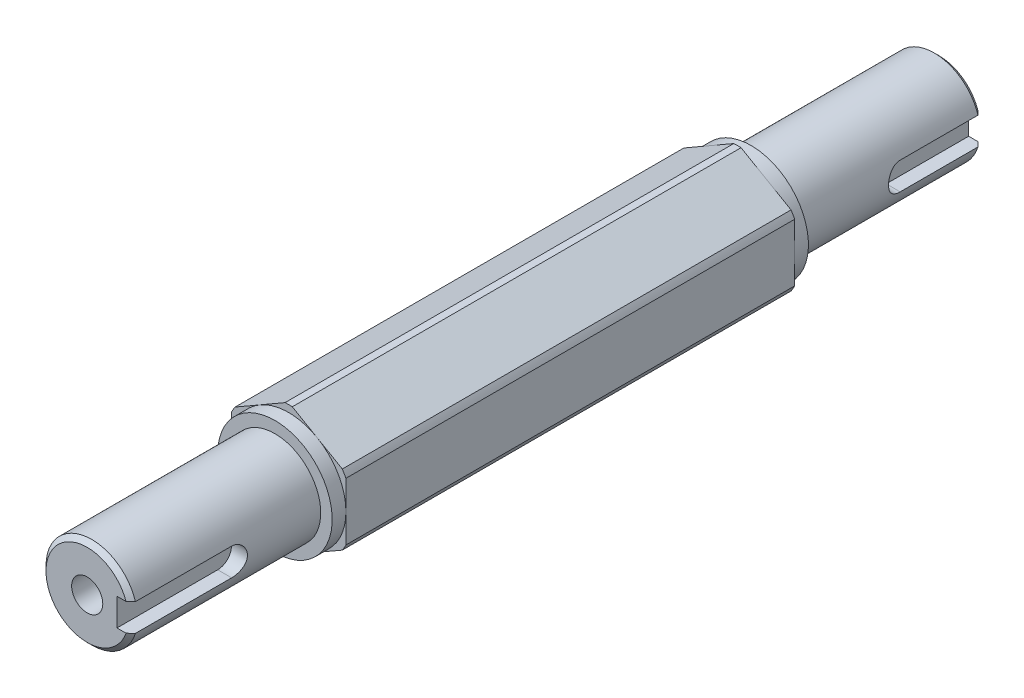
SolidWorks part; units mm, degrees
ref_plane "Front Plane" through (0, 0, 0) normal (0, 0, 1) x (1, 0, 0)
ref_plane "Top Plane" through (0, 0, 0) normal (0, 1, 0) x (1, 0, 0)
ref_plane "Right Plane" through (0, 0, 0) normal (1, 0, 0) x (0, 0, -1)
sketch "Sketch1" plane through (0, 0, 0) normal (0, 0, 1) x (1, 0, 0)
  line L1 (0, 14.4338) -> (-12.5, 7.2169)
  line L2 (-12.5, 7.2169) -> (-12.5, -7.2169)
  line L3 (-12.5, -7.2169) -> (0, -14.4338)
  line L4 (0, -14.4338) -> (12.5, -7.2169)
  line L5 (12.5, -7.2169) -> (12.5, 7.2169)
  line L6 (12.5, 7.2169) -> (0, 14.4338)
  circle A0 centre (0, 0) radius 12.5 construction
  circle A1 centre (0, 0) radius 14
  dimension "D1" = 28
  dimension "D2" = 25
extrude "Boss-Extrude1" add sketch "Sketch1" along normal mid plane 98 contours L5 A1 L6 L1 L2 L3 L4
sketch "Sketch2" plane through (0, 0, 0) normal (1, 0, 0) x (0, 0, -1)
  line L0 (70.7525, 0) -> (-133.0929, 0) construction
  line L1 (-93, 0) -> (-93, 10)
  line L2 (-93, 10) -> (-52, 10)
  line L4 (-49, 12.5) -> (-49, 0)
  line L5 (-49, 0) -> (-93, 0)
  line L6 (52, 10) -> (93, 10)
  line L7 (49, -6.3048) -> (49, 6.3048) construction
  line L8 (93, 10) -> (93, 0)
  line L11 (93, 0) -> (49, 0)
  line L12 (49, 0) -> (49, 12.5)
  line L14 (-52, 10) -> (-52, 12.5)
  line L15 (-52, 12.5) -> (-49, 12.5)
  line L16 (-49, 7.6729) -> (-49, 13.9777) construction
  line L17 (52, 10) -> (52, 12.5)
  line L18 (52, 12.5) -> (49, 12.5)
  dimension "D1" = 20
  dimension "D2" = 25
  dimension "D3" = 104
  dimension "D4" = 41
  dimension "D7" = 41
revolve "Revolve1" add sketch "Sketch2" angle 360 about L0
chamfer "Chamfer1" distance 1 angle 45 2 edges at (-10, 0, 93) (-10, 0, -93)
hole_wizard "M8 Tapped Hole1" positions "3DSketch1" profile "Sketch3" tap size "M8" standard "ISO"
sketch3d "3DSketch1"
  circle A0 centre (0, 0, 93) radius 9 construction
  point P0 (0, 0, 93)
  point P5 (0, 0, 102)
sketch "Sketch3" plane through (0, 0, 93) normal (1, 0, 0) x (0, -1, 0)
  line L0 (0, 0) -> (0, 21.7929)
  line L1 (0, 21.7929) -> (3.4, 19.75)
  line L2 (3.4, 19.75) -> (3.4, 0)
  line L5 (3.4, 0) -> (0, 0)
  line L10 (0, 21.7929) -> (-3.4, 19.75) construction
  line L11 (0, -6.35) -> (0, 107.95) construction
  dimension "Tap Drill Dia." = 6.8
  dimension "Tap Drill Depth" = 19.75
  dimension "Drill Angle" = 118
cosmetic thread "Hole Thread1" parameters "D1"=16, "D2"=8
sketch "Sketch4" plane through (0, 0, 0) normal (1, 0, 0) x (0, 0, -1)
  line L0 (-93, 0) -> (-71, 0) construction
  line L2 (-93, -3) -> (-71, -3)
  line L3 (-93, 3) -> (-71, 3)
  line L4 (93, 0) -> (75, 0) construction
  line L5 (93, -9) -> (93, 9) construction
  line L6 (93, 3) -> (75, 3)
  line L7 (93, -3) -> (75, -3)
  line L8 (-93, 9) -> (-93, -9) construction
  arc A0 (-93, -3) -> (-93, 3) centre (-93, 0) cw
  arc A1 (-71, -3) -> (-71, 3) centre (-71, 0) ccw
  arc A2 (93, 3) -> (93, -3) centre (93, 0) cw
  arc A3 (75, 3) -> (75, -3) centre (75, 0) ccw
  dimension "D6" = 3
  dimension "D1" = 22
  dimension "D5" = 18
  dimension "D3" = 3
  dimension "D4" = 3
  dimension "D7" = 3
extrude "Cut-Extrude1" cut sketch "Sketch4" against normal blind 3.5 from offset 10
